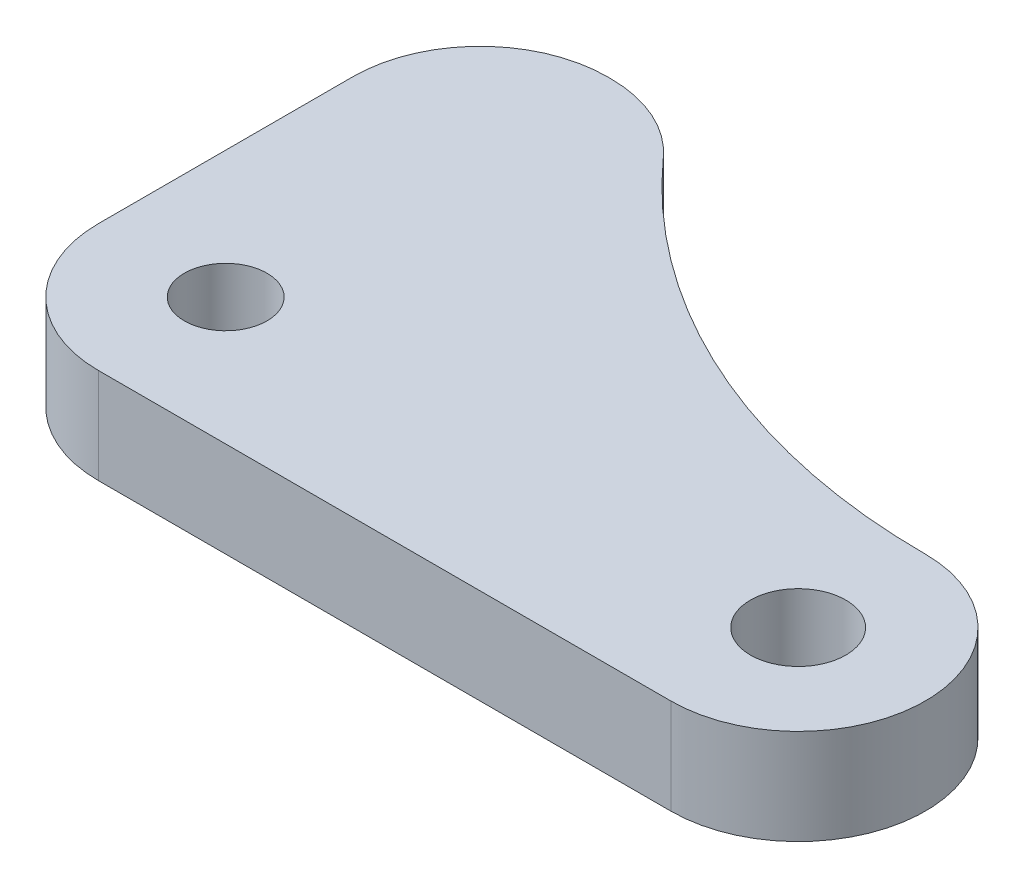
SolidWorks part; units mm, degrees
ref_plane "Plano frontal" through (0, 0, 0) normal (0, 0, 1) x (1, 0, 0)
ref_plane "Plano superior" through (0, 0, 0) normal (0, 1, 0) x (1, 0, 0)
ref_plane "Plano direito" through (0, 0, 0) normal (1, 0, 0) x (0, 0, -1)
sketch "Esboço1" plane through (0, 0, 0) normal (0, 1, 0) x (1, 0, 0)
  line L0 (-9, 0) -> (9, 0) construction
  line L1 (-9, -4) -> (9, -4)
  line L2 (-8.8885, 12) -> (-9, 12)
  line L3 (-13, 8) -> (-13, 0)
  arc A0 (9, -4) -> (9, 4) centre (9, 0) ccw
  arc A1 (9, 4) -> (-5.9071, 10.6667) centre (9, 24) cw
  arc A2 (-5.9071, 10.6667) -> (-8.8885, 12) centre (-8.8885, 8) ccw
  arc A3 (-9, 12) -> (-13, 8) centre (-9, 8) ccw
  arc A4 (-13, 0) -> (-9, -4) centre (-9, 0) ccw
  point P4 (0, 0)
  dimension "D5" = 20
  dimension "D1" = 18
  dimension "D2" = 16
  dimension "D3" = 8
  dimension "D4" = 26
extrude "Ressalto-extrusão1" add sketch "Esboço1" along normal blind 3
hole_wizard "Furo de diâmetro Ø3.0 (3)1" positions "Esboço2" profile "Esboço3" hole size "Ø3.0" standard "ISO" end condition through all
sketch "Esboço2" plane through (0, 3, 0) normal (0, 1, 0) x (1, 0, 0)
  point P0 (9, 0)
sketch "Esboço3" plane through (9, 3, 0) normal (1, 0, 0) x (0, 0, 1)
  line L0 (0, 0) -> (0, 3)
  line L1 (0, 3) -> (1.5, 3)
  line L2 (1.5, 3) -> (1.5, 0)
  line L5 (1.5, 0) -> (0, 0)
  line L11 (0, -6.35) -> (0, 107.95) construction
  dimension "Thru Hole Dia." = 3
  dimension "Thru Hole Depth" = 3
hole_wizard "Furo de diâmetro Ø2.6 (2.6)1" positions "Esboço4" profile "Esboço5" hole size "Ø2.6" standard "ISO" end condition through all
sketch "Esboço4" plane through (0, 3, 0) normal (0, 1, 0) x (1, 0, 0)
  point P0 (-9, 0)
sketch "Esboço5" plane through (-9, 3, 0) normal (1, 0, 0) x (0, 0, 1)
  line L0 (0, 0) -> (0, 3)
  line L1 (0, 3) -> (1.3, 3)
  line L2 (1.3, 3) -> (1.3, 0)
  line L5 (1.3, 0) -> (0, 0)
  line L11 (0, -6.35) -> (0, 107.95) construction
  dimension "Thru Hole Dia." = 2.6
  dimension "Thru Hole Depth" = 3
